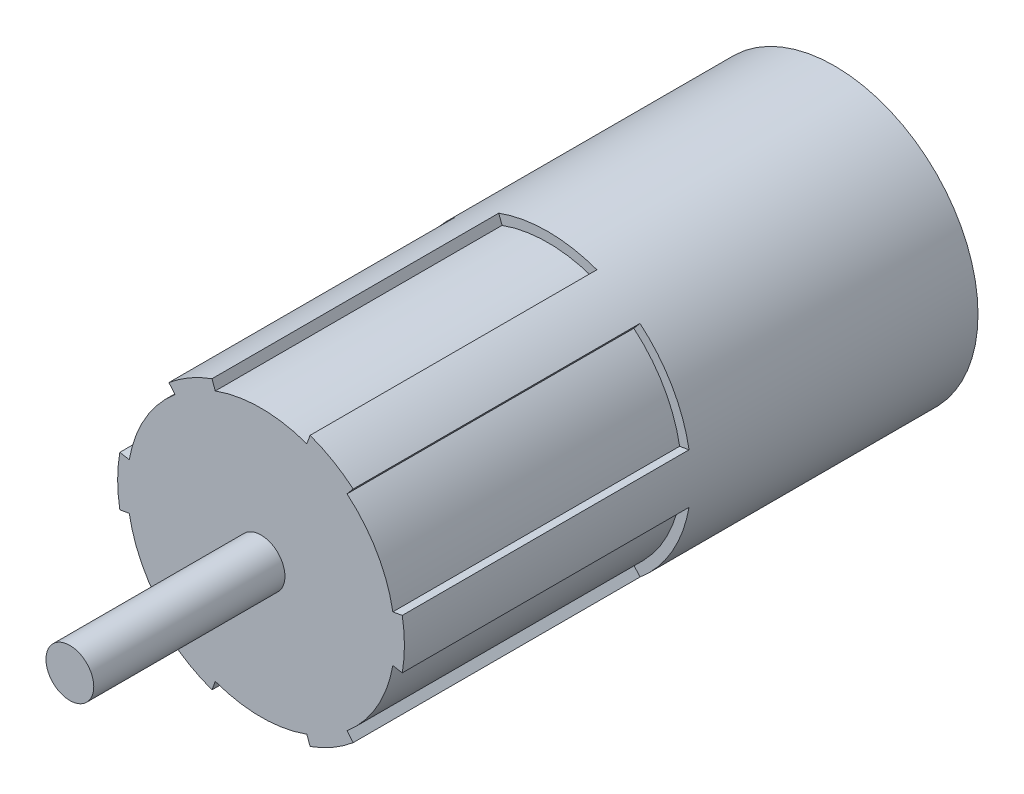
SolidWorks part; units mm, degrees
ref_plane "Front Plane" through (0, 0, 0) normal (0, 0, 1) x (1, 0, 0)
ref_plane "Top Plane" through (0, 0, 0) normal (0, 1, 0) x (1, 0, 0)
ref_plane "Right Plane" through (0, 0, 0) normal (1, 0, 0) x (0, 0, -1)
sketch "Sketch1" plane through (0, 0, 0) normal (0, 0, 1) x (1, 0, 0)
  circle A0 centre (0, 0) radius 15
  dimension "D1" = 30
extrude "Boss-Extrude1" add sketch "Sketch1" along normal mid plane 60
sketch "Sketch2" plane through (0, 0, 30) normal (0, 0, 1) x (1, 0, 0)
  circle A0 centre (0, 0) radius 2.5
  dimension "D1" = 5
extrude "Boss-Extrude2" add sketch "Sketch2" along normal blind 20
sketch "Sketch4" plane through (0, 0, 30) normal (0, 0, 1) x (1, 0, 0)
  line L0 (-4.7883, 13.1557) -> (-5.1303, 14.0954)
  line L1 (4.7883, 13.1557) -> (5.1303, 14.0954)
  line L2 (0, 14) -> (0, 0) construction
  line L3 (4.7883, 13.1557) -> (0, 0) construction
  arc A0 (-4.7883, 13.1557) -> (4.7883, 13.1557) centre (0, 0) cw
  arc A1 (-5.1303, 14.0954) -> (5.1303, 14.0954) centre (0, 0) cw
  circle A2 centre (0, 0) radius 15 construction
  dimension "D1" = 14
  dimension "D2" = 20
extrude "Cut-Extrude2" cut sketch "Sketch4" against normal blind 30
pattern_circular "CirPattern2" count 6 over 360 about axis through (0, 0, 0) along (0, 0, 1) of "Cut-Extrude2"
